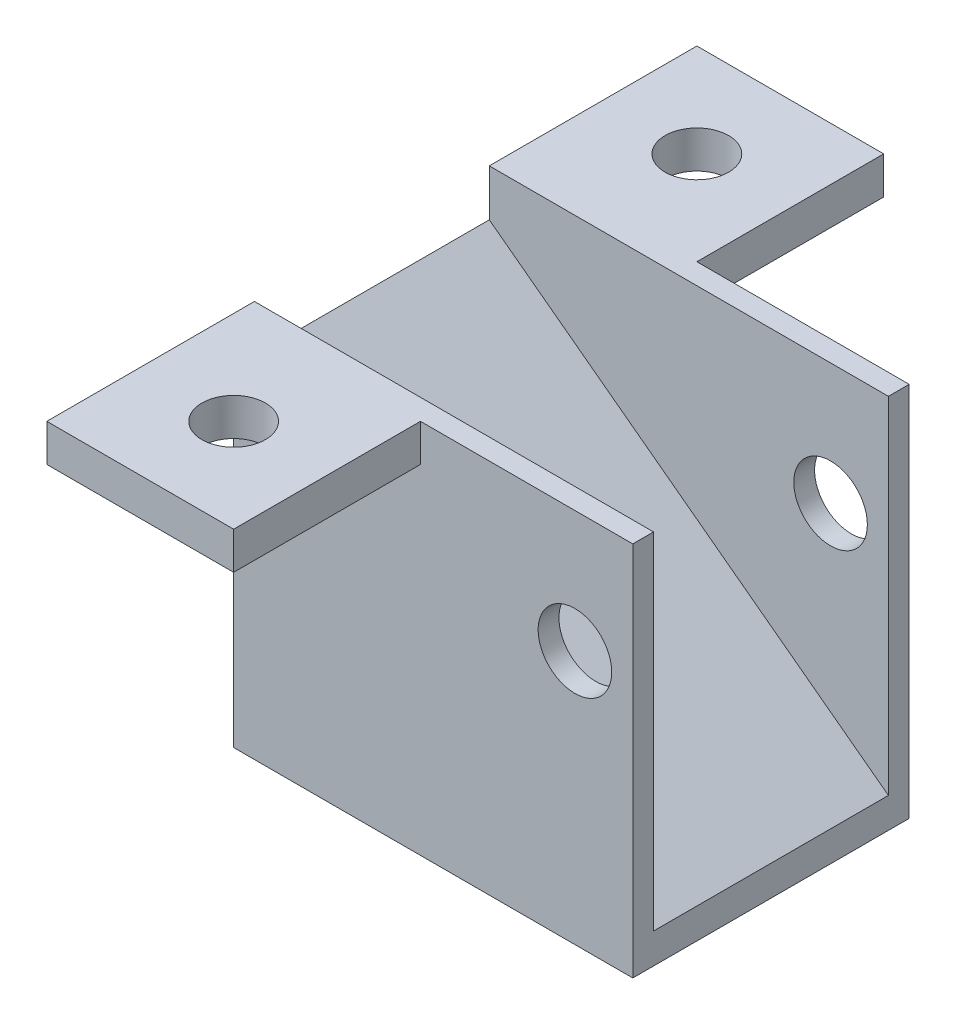
SolidWorks part; units mm, degrees
ref_plane "Front Plane" through (0, 0, 0) normal (0, 0, 1) x (1, 0, 0)
ref_plane "Top Plane" through (0, 0, 0) normal (0, 1, 0) x (1, 0, 0)
ref_plane "Right Plane" through (0, 0, 0) normal (1, 0, 0) x (0, 0, -1)
sketch "Sketch8" plane through (0, 0, 0) normal (0, 1, 0) x (1, 0, 0)
  line L0 (-44.9741, -2.9009) -> (-44.9741, -40.7469)
  line L1 (-44.9741, -40.7469) -> (2.1658, -40.7469)
  line L2 (2.1658, -40.7469) -> (2.1658, -35.808)
  line L3 (2.1658, -2.9009) -> (-44.9741, -2.9009)
  line L4 (2.1658, -7.8398) -> (6.7556, -12.4295)
  line L5 (2.1658, -7.8398) -> (2.1658, -2.9009)
  line L6 (6.7556, -31.2182) -> (2.1658, -35.808)
  line L7 (6.7556, -12.4295) -> (33.8879, -12.4295)
  line L8 (33.8879, -12.4295) -> (33.8879, -31.2182)
  line L9 (33.8879, -31.2182) -> (6.7556, -31.2182)
  line L10 (-44.9741, -21.8239) -> (33.8879, -21.8239) construction
  dimension "D1" = 37.846
  dimension "D2" = 47.1399
  dimension "D3" = 45
  dimension "D4" = 45
  dimension "D5" = 4.5898
  dimension "D6" = 18.923
  dimension "D7" = 4.9389
  dimension "D8" = 78.8619
extrude "Boss-Extrude6" add sketch "Sketch8" along normal blind 2.0599
sketch "Sketch9" plane through (0, 2.0599, 0) normal (0, 1, 0) x (1, 0, 0)
  line L0 (33.8879, -13.8418) -> (6.7556, -13.8418)
  line L1 (33.8879, -31.2182) -> (33.8879, -12.4295) construction
  line L2 (6.7556, -13.8418) -> (6.7556, -12.4295)
  line L3 (6.7556, -12.4295) -> (33.8879, -12.4295)
  line L4 (33.8879, -12.4295) -> (33.8879, -13.8418)
  line L5 (6.7556, -31.2182) -> (6.7556, -29.806)
  line L6 (6.7556, -29.806) -> (33.8879, -29.806)
  line L7 (33.8879, -29.806) -> (33.8879, -31.2182)
  line L8 (33.8879, -31.2182) -> (6.7556, -31.2182)
  dimension "D1" = 1.4122
  dimension "D2" = 1.4122
extrude "Boss-Extrude7" add sketch "Sketch9" along normal blind 20.32
sketch "Sketch10" plane through (0, 0, 31.2182) normal (0, 0, 1) x (1, 0, 0)
  line L0 (6.7556, 0) -> (33.8879, 0) construction
  line L1 (-44.9741, 2.0599) -> (-44.9741, 0) construction
  circle A0 centre (29.9559, 17.2847) radius 2.5006
  dimension "D2" = 74.93
  dimension "D1" = 17.2847
extrude "Cut-Extrude3" cut sketch "Sketch10" against normal blind 25.4
sketch "Sketch14" plane through (0, 0, 13.8418) normal (0, 0, 1) x (1, 0, 0)
  line L0 (6.7556, 22.3799) -> (33.8879, 2.0599)
  line L1 (6.7556, 22.3799) -> (6.7556, 19.8268)
  line L2 (6.7556, 22.3799) -> (6.7556, 2.0599) construction
  line L3 (6.7556, 19.8268) -> (30.5689, 2.0599)
  line L4 (30.5689, 2.0599) -> (33.8879, 2.0599)
extrude "Boss-Extrude10" add sketch "Sketch14" along normal blind 16.0299
sketch "Sketch15" plane through (0, 2.0599, 0) normal (0, 1, 0) x (1, 0, 0)
  line L0 (6.7556, -29.806) -> (6.7556, -13.8418) construction
  line L1 (-44.9741, -40.7469) -> (6.7556, -40.7469)
  line L2 (-44.9741, -40.7469) -> (-44.9741, -2.9009)
  line L3 (-44.9741, -2.9009) -> (6.7556, -2.9009)
  line L4 (6.7556, -40.7469) -> (6.7556, -2.9009)
  line L5 (2.1658, -2.9009) -> (-44.9741, -2.9009) construction
extrude "Cut-Extrude5" cut sketch "Sketch15" against normal through all
ref_plane "Plane2" through (6.7556, 0, 31.2182) normal (1, 0, 0) x (0, 0, -1)
sketch "Sketch16" plane through (0, 22.3799, 0) normal (0, 1, 0) x (1, 0, 0)
  line L0 (33.8879, -31.2182) -> (33.8879, -29.806) construction
  line L1 (33.8879, -29.806) -> (6.7556, -29.806) construction
  line L2 (6.7556, -29.806) -> (6.7556, -31.2182) construction
  line L3 (6.7556, -31.2182) -> (33.8879, -31.2182) construction
  line L4 (33.8879, -13.8418) -> (33.8879, -12.4295) construction
  line L5 (33.8879, -12.4295) -> (6.7556, -12.4295) construction
  line L6 (6.7556, -12.4295) -> (6.7556, -13.8418) construction
  line L7 (6.7556, -13.8418) -> (33.8879, -13.8418) construction
  line L8 (33.8879, -31.2182) -> (33.8879, -29.806)
  line L9 (33.8879, -29.806) -> (6.7556, -29.806)
  line L10 (6.7556, -29.806) -> (6.7556, -31.2182)
  line L11 (6.7556, -31.2182) -> (33.8879, -31.2182)
  line L12 (33.8879, -13.8418) -> (33.8879, -12.4295)
  line L13 (33.8879, -12.4295) -> (6.7556, -12.4295)
  line L14 (6.7556, -12.4295) -> (6.7556, -13.8418)
  line L15 (6.7556, -13.8418) -> (33.8879, -13.8418)
extrude "Boss-Extrude11" add sketch "Sketch16" along normal blind 3.175
sketch "Sketch18" plane through (0, 0, 31.2182) normal (0, 0, 1) x (1, 0, 0)
  line L1 (6.7556, 25.5549) -> (19.4556, 25.5549)
  line L2 (6.7556, 25.5549) -> (6.7556, 23.0149)
  line L3 (6.7556, 23.0149) -> (19.4556, 23.0149)
  line L4 (19.4556, 25.5549) -> (19.4556, 23.0149)
  dimension "D1" = 12.7
  dimension "D2" = 2.54
extrude "Boss-Extrude12" add sketch "Sketch18" along normal blind 12.7
ref_plane "Plane3" through (0, 0, 21.8239) normal (0, 0, 1) x (1, 0, 0)
mirror "Mirror1" about plane through (0, 0, 21.8239) normal (0, 0, 1) of "Boss-Extrude12"
sketch "Sketch19" plane through (0, 25.5549, 0) normal (0, 1, 0) x (1, 0, 0)
  line L0 (19.4556, 0.2705) -> (19.4556, -12.4295) construction
  line L1 (19.4556, 0.2705) -> (6.7556, 0.2705) construction
  line L2 (-12.9223, -21.8239) -> (12.9223, -21.8239) construction
  circle A0 centre (13.1056, -6.0795) radius 2.159
  circle A1 centre (13.1056, -37.5682) radius 2.159
  dimension "D1" = 4.318
  dimension "D2" = 6.35
  dimension "D3" = 6.35
extrude "Cut-Extrude6" cut sketch "Sketch19" against normal through all
